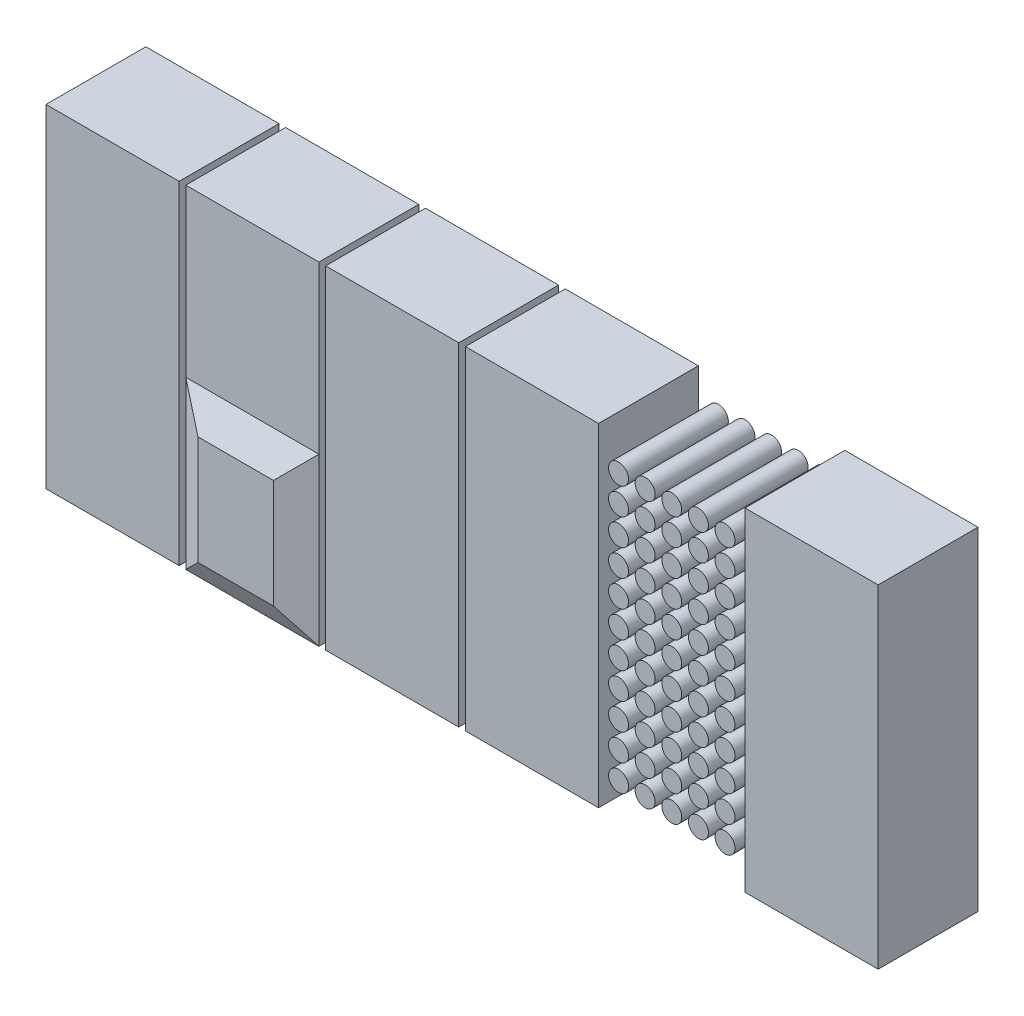
SolidWorks part; units mm, degrees
ref_plane "Front Plane" through (0, 0, 0) normal (0, 0, 1) x (1, 0, 0)
ref_plane "Top Plane" through (0, 0, 0) normal (0, 1, 0) x (1, 0, 0)
ref_plane "Right Plane" through (0, 0, 0) normal (1, 0, 0) x (0, 0, -1)
sketch "Sketch2" plane through (0, 0, 0) normal (0, 0, 1) x (1, 0, 0)
  line L0 (1100, 2500) -> (1100, -2500)
  line L1 (-1000, 2500) -> (1000, 2500)
  line L2 (-1000, 2500) -> (-1000, -2500)
  line L3 (-1000, -2500) -> (1000, -2500)
  line L4 (1000, 2500) -> (1000, -2500)
  line L5 (-1000, 2500) -> (1000, -2500) construction
  line L6 (-1000, -2500) -> (1000, 2500) construction
  line L7 (1100, 2500) -> (3100, 2500)
  line L8 (3100, 2500) -> (3100, -2500)
  line L9 (1100, -2500) -> (3100, -2500)
  line L10 (3200, 2500) -> (3200, -2500)
  line L11 (3200, 2500) -> (5200, 2500)
  line L12 (5200, 2500) -> (5200, -2500)
  line L13 (3200, -2500) -> (5200, -2500)
  line L14 (5300, 2500) -> (5300, -2500)
  line L15 (5300, 2500) -> (7300, 2500)
  line L16 (7300, 2500) -> (7300, -2500)
  line L17 (5300, -2500) -> (7300, -2500)
  line L18 (7400, 2500) -> (7400, -2500)
  line L19 (7400, 2500) -> (9400, 2500)
  line L20 (9400, 2500) -> (9400, -2500)
  line L21 (7400, -2500) -> (9400, -2500)
  line L22 (9500, 2500) -> (9500, -2500)
  line L23 (9500, 2500) -> (11500, 2500)
  line L24 (11500, 2500) -> (11500, -2500)
  line L25 (9500, -2500) -> (11500, -2500)
  line L26 (8400, 2500) -> (8400, -2500) construction
  line L27 (7400, 0) -> (9400, 0) construction
  circle A0 centre (8400, 0) radius 150
  circle A1 centre (8800, 0) radius 150
  circle A2 centre (9200, 0) radius 150
  circle A3 centre (8800, 400) radius 150
  circle A4 centre (9200, 400) radius 150
  circle A5 centre (8800, 800) radius 150
  circle A6 centre (9200, 800) radius 150
  circle A7 centre (8800, 1200) radius 150
  circle A8 centre (9200, 1200) radius 150
  circle A9 centre (8800, 1600) radius 150
  circle A10 centre (9200, 1600) radius 150
  circle A11 centre (8800, 2000) radius 150
  circle A12 centre (9200, 2000) radius 150
  circle A13 centre (8400, 400) radius 150
  circle A14 centre (8400, 800) radius 150
  circle A15 centre (8400, 1200) radius 150
  circle A16 centre (8400, 1600) radius 150
  circle A17 centre (8400, 2000) radius 150
  circle A18 centre (7600, 0) radius 150
  circle A19 centre (8000, 0) radius 150
  circle A20 centre (7600, 400) radius 150
  circle A21 centre (8000, 400) radius 150
  circle A22 centre (7600, 800) radius 150
  circle A23 centre (8000, 800) radius 150
  circle A24 centre (7600, 1200) radius 150
  circle A25 centre (8000, 1200) radius 150
  circle A26 centre (7600, 1600) radius 150
  circle A27 centre (8000, 1600) radius 150
  circle A28 centre (7600, 2000) radius 150
  circle A29 centre (8000, 2000) radius 150
  circle A30 centre (8400, -400) radius 150
  circle A31 centre (9200, -400) radius 150
  circle A32 centre (8800, -400) radius 150
  circle A33 centre (8000, -400) radius 150
  circle A34 centre (7600, -400) radius 150
  circle A35 centre (9200, -800) radius 150
  circle A36 centre (8800, -800) radius 150
  circle A37 centre (8400, -800) radius 150
  circle A38 centre (8000, -800) radius 150
  circle A39 centre (7600, -800) radius 150
  circle A40 centre (7600, -1200) radius 150
  circle A41 centre (8000, -1200) radius 150
  circle A42 centre (8400, -1200) radius 150
  circle A43 centre (8800, -1200) radius 150
  circle A44 centre (9200, -1200) radius 150
  circle A45 centre (9200, -1600) radius 150
  circle A46 centre (8800, -1600) radius 150
  circle A47 centre (8400, -1600) radius 150
  circle A48 centre (8000, -1600) radius 150
  circle A49 centre (7600, -1600) radius 150
  circle A50 centre (9200, -2000) radius 150
  circle A51 centre (8800, -2000) radius 150
  circle A52 centre (8400, -2000) radius 150
  circle A53 centre (8000, -2000) radius 150
  circle A54 centre (7600, -2000) radius 150
  point P0 (0, 0)
  point P140 (0, 0)
  dimension "D4" = 300
  dimension "D1" = 2000
  dimension "D2" = 5000
  dimension "D3" = 6
  dimension "D5" = 3
  dimension "D6" = 6
extrude "Boss-Extrude1" add sketch "Sketch2" along normal blind 1500 contours L4 L1 L2 L3 | L0 L9 L8 L7 | L10 L13 L12 L11 | L14 L17 L16 L15 | L22 L25 L24 L23 | A54 | A49 | A40 | A39 | A34 | A18 | A20 | A22 | A24 | A26 | A27 | A29 | A25 | A23 | A21 | A19 | A33 | A38 | A41 | A48 | A53 | A52 | A42 | A37 | A30 | A13 | A14 | A15 | A16 | A17 | A11 | A9 | A7 | A5 | A3 | A1 | A43 | A46 | A51 | A50 | A45 | A44 | A31 | A4 | A6 | A8 | A10 | A28 | A47 | A0 | A32 | A36 | A35 | A2 | A12
sketch "Sketch3" plane through (0, 0, 1500) normal (0, 0, 1) x (1, 0, 0)
  line L0 (1100, 2500) -> (1100, -2500) construction
  line L1 (1100, 0) -> (3100, 0)
  line L2 (1100, 0) -> (1100, -2500)
  line L3 (1100, -2500) -> (3100, -2500)
  line L4 (3100, 0) -> (3100, -2500)
extrude "Boss-Extrude2" add sketch "Sketch3" along normal blind 250 draft 60
